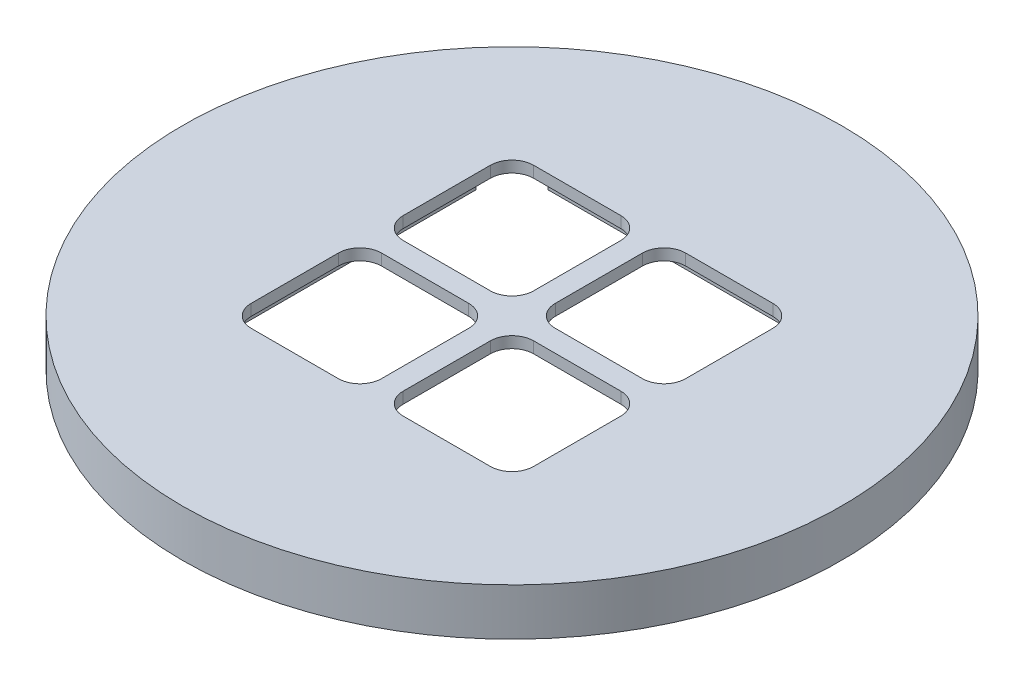
SolidWorks part; units mm, degrees
material "ABS"
ref_plane "Front Plane" through (0, 0, 0) normal (0, 0, 1) x (1, 0, 0)
ref_plane "Top Plane" through (0, 0, 0) normal (0, 1, 0) x (1, 0, 0)
ref_plane "Right Plane" through (0, 0, 0) normal (1, 0, 0) x (0, 0, -1)
sketch "Sketch2" plane through (0, 0, 0) normal (0, 1, 0) x (1, 0, 0)
  line L1 (-12.1337, 8.6287) -> (-30.6337, 8.6287)
  line L2 (-12.1337, 8.6287) -> (-12.1337, -9.8713)
  line L3 (-12.1337, -9.8713) -> (-30.6337, -9.8713)
  line L4 (-30.6337, 8.6287) -> (-30.6337, -9.8713)
  line L5 (-12.1337, 8.6287) -> (-30.6337, -9.8713) construction
  line L6 (-12.1337, -9.8713) -> (-30.6337, 8.6287) construction
  circle A0 centre (-21.3837, -0.6213) radius 17.5
  dimension "D2" = 35
  dimension "D3" = 21.3837
  dimension "D4" = 18.5
extrude "Boss-Extrude1" add sketch "Sketch2" along normal blind 2.5
sketch "Sketch4" plane through (0, 0, 0) normal (0, -1, 0) x (1, 0, 0)
  circle A0 centre (-21.5697, 15.5896) radius 1.67
  dimension "D1" = 3.34
extrude "Cut-Extrude1" cut sketch "Sketch4" against normal blind 1.15
pattern_circular "CirPattern1" count 4 over 360 about axis through (-21.3837, 0, 0.6213) along (0, 1, 0) of "Cut-Extrude1"
sketch "Sketch5" plane through (0, 2.5, 0) normal (0, 1, 0) x (1, 0, 0)
  line L1 (-13.8837, 6.8787) -> (-28.8837, 6.8787)
  line L2 (-13.8837, 6.8787) -> (-13.8837, -8.1213)
  line L3 (-13.8837, -8.1213) -> (-28.8837, -8.1213)
  line L4 (-28.8837, 6.8787) -> (-28.8837, -8.1213)
  line L5 (-13.8837, 6.8787) -> (-28.8837, -8.1213) construction
  line L6 (-13.8837, -8.1213) -> (-28.8837, 6.8787) construction
  point P0 (-21.3837, -0.6213)
  line M1 (-30.6337, -9.8713) -> (-30.6337, 8.6287)
  line M2 (-30.6337, 8.6287) -> (-12.1337, 8.6287)
  line M3 (-12.1337, 8.6287) -> (-12.1337, -9.8713)
  line M4 (-12.1337, -9.8713) -> (-30.6337, -9.8713)
  dimension "D1" = 15
  dimension "D2" = 15
extrude "Boss-Extrude2" add sketch "Sketch5" against normal blind 0.6 contours L4 L1 L2 L3 M1 M4 M3 M2
sketch "Sketch10" plane through (0, 2.5, 0) normal (0, 1, 0) x (1, 0, 0)
  line L0 (-28.8837, 6.8787) -> (-13.8837, -8.1213) construction
  line L1 (-28.8837, 6.8787) -> (-13.8837, 6.8787)
  line L2 (-28.8837, 6.8787) -> (-28.8837, -8.1213)
  line L3 (-28.8837, -8.1213) -> (-13.8837, -8.1213)
  line L4 (-13.8837, 6.8787) -> (-13.8837, -8.1213)
  line L5 (-28.8837, -8.1213) -> (-13.8837, 6.8787) construction
  line L7 (-21.9587, -8.1213) -> (-20.8087, -8.1213)
  line L8 (-21.9587, -8.1213) -> (-21.9587, 6.8787)
  line L9 (-21.9587, 6.8787) -> (-20.8087, 6.8787)
  line L10 (-20.8087, -8.1213) -> (-20.8087, 6.8787)
  line L11 (-21.9587, -8.1213) -> (-20.8087, 6.8787) construction
  line L12 (-21.9587, 6.8787) -> (-20.8087, -8.1213) construction
  line L13 (-28.8837, -1.1963) -> (-13.8837, -1.1963)
  line L14 (-28.8837, -1.1963) -> (-28.8837, -0.0463)
  line L15 (-28.8837, -0.0463) -> (-13.8837, -0.0463)
  line L16 (-13.8837, -1.1963) -> (-13.8837, -0.0463)
  line L17 (-28.8837, -1.1963) -> (-13.8837, -0.0463) construction
  line L18 (-28.8837, -0.0463) -> (-13.8837, -1.1963) construction
  point P6 (-21.3837, -0.6213)
  point P11 (-21.3837, -0.6213)
  dimension "D1" = 1.15
  dimension "D2" = 1.15
extrude "Boss-Extrude4" add sketch "Sketch10" against normal up to surface (0.6 mm away) contours L8 L15 L10 L1 | L13 L8 L3 L10 | L15 L8 L13 L10 | L15 L10 L13 L4 | L15 L2 L13 L8 up to face at (-21.3837, 1.9, 0.6213)
fillet "Fillet1" radius 1.15 16 edges at (-21.9587, 2.2, 8.1213) (-20.8087, 2.2, 8.1213) (-20.8087, 2.2, 1.1963) (-28.8837, 2.2, 1.1963) (-13.8837, 2.2, 1.1963) (-21.9587, 2.2, 1.1963) (-21.9587, 2.2, -6.8787) (-28.8837, 2.2, 0.0463) (-21.9587, 2.2, 0.0463) (-13.8837, 2.2, 0.0463) (-20.8087, 2.2, 0.0463) (-20.8087, 2.2, -6.8787) (-13.8837, 2.2, 8.1213) (-28.8837, 2.2, 8.1213) (-28.8837, 2.2, -6.8787) (-13.8837, 2.2, -6.8787)
sketch "Sketch11" plane through (0, 0, 0) normal (0, -1, 0) x (1, 0, 0)
  line L0 (-30.6337, 9.8713) -> (-30.1337, 9.8713) construction
  line L1 (-12.1337, 9.8713) -> (-30.6337, 9.8713) construction
  line L2 (-30.1337, 9.8713) -> (-30.1337, 9.3713) construction
  circle A0 centre (-30.1337, 9.3713) radius 1.5
  dimension "D2" = 3
  dimension "D1" = 0.5
extrude "Cut-Extrude2" cut sketch "Sketch11" against normal up to surface (1.9 mm away)
pattern_circular "CirPattern2" count 4 over 360 about axis through (-21.3837, 0, 0.6213) along (0, 1, 0) of "Cut-Extrude2"
